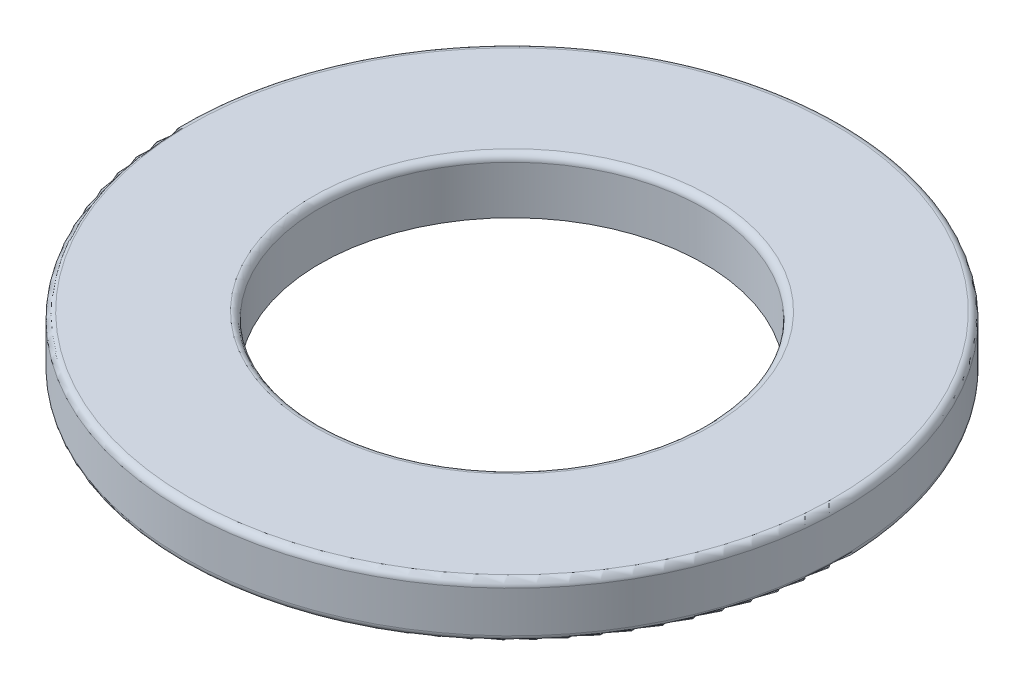
SolidWorks part; units mm, degrees
ref_plane "Front Plane" through (0, 0, 0) normal (0, 0, 1) x (1, 0, 0)
ref_plane "Top Plane" through (0, 0, 0) normal (0, 1, 0) x (1, 0, 0)
ref_plane "Right Plane" through (0, 0, 0) normal (1, 0, 0) x (0, 0, -1)
sketch "Sketch1" plane through (0, 0, 0) normal (0, 1, 0) x (1, 0, 0)
  circle A0 centre (0, 0) radius 12
  dimension "D1" = 24
extrude "Boss-Extrude1" add sketch "Sketch1" along normal blind 2
sketch "Sketch2" plane through (0, 2, 0) normal (0, 1, 0) x (1, 0, 0)
  circle A0 centre (0, 0) radius 7
  dimension "D1" = 14
extrude "Cut-Extrude1" cut sketch "Sketch2" against normal through all
fillet "Fillet1" radius 0.25 3 edges at (0, 0, 12) (0, 2, 7) (0, 2, 12)
